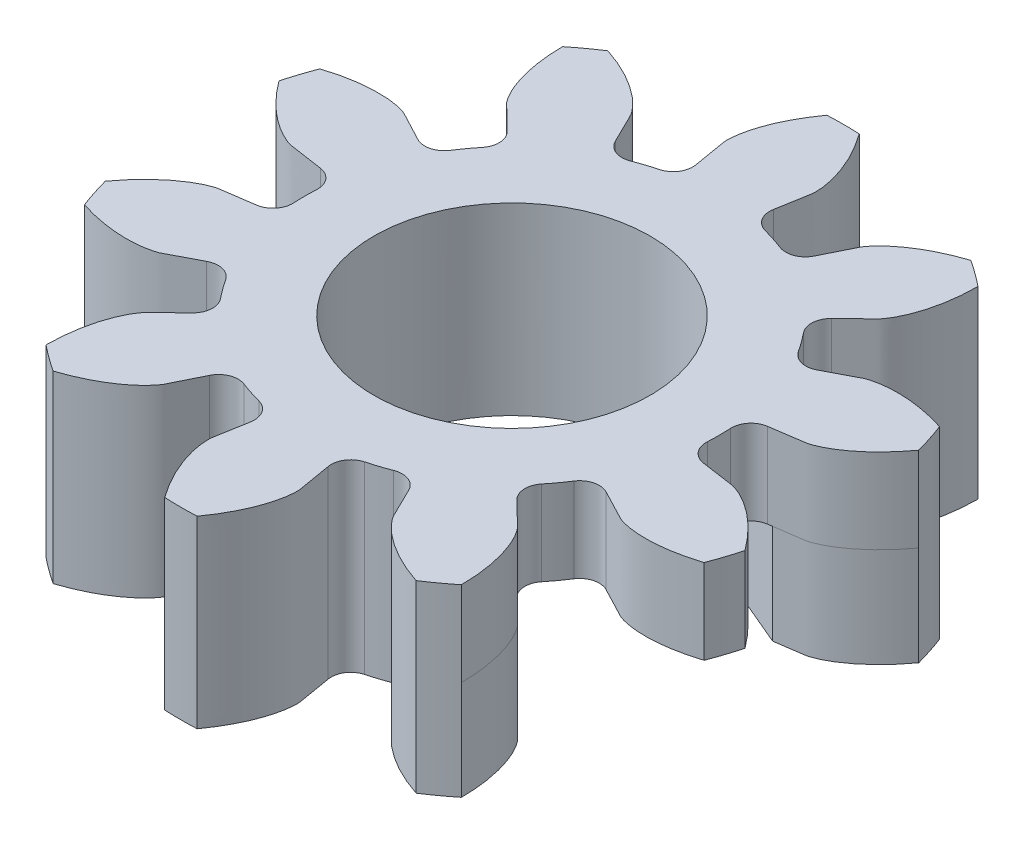
SolidWorks part; units mm, degrees
ref_plane "前视基准面" through (0, 0, 0) normal (0, 0, 1) x (1, 0, 0)
ref_plane "上视基准面" through (0, 0, 0) normal (0, 1, 0) x (1, 0, 0)
ref_plane "右视基准面" through (0, 0, 0) normal (1, 0, 0) x (0, 0, -1)
ref_plane "基准面1" through (0, -5, 0) normal (0, -1, 0) x (1, 0, 0)
sketch "草图1" plane through (0, -5, 0) normal (0, -1, 0) x (1, 0, 0)
  line L0 (6.1909, -0.8847) -> (3.0118, -2.2341)
  line L1 (1.1234, 3.5778) -> (4.4885, 4.3547)
  arc A0 (5.6398, 7.0137) -> (8.6853, -2.3592) centre (0, 0) ccw
  arc A1 (3.0118, -2.2341) -> (1.1234, 3.5778) centre (0, 0) ccw
  spline S0 degree 3 poles (6.1909, -0.8847) (6.5939, -0.9417) (6.9799, -0.9969) (7.0084, -1.0053) (7.0566, -1.0179) (7.1132, -1.0368) (7.1879, -1.0654) (7.2763, -1.1046) (7.3786, -1.1562) (7.4935, -1.2216) (7.6198, -1.3021) (7.7564, -1.399) (7.9018, -1.5135) (8.0545, -1.6467) (8.2131, -1.7996) (8.3759, -1.9733) (8.5348, -2.1595) (8.6367, -2.2945) (8.6853, -2.3592) knots 0.057559 0.057559 0.057559 0.057559 0.176646 0.200647 0.231632 0.268294 0.309864 0.355822 0.405784 0.459451 0.516584 0.576985 0.640485 0.70694 0.776225 0.848227 0.922848 0.990951 0.990951 0.990951 0.990951
  spline S1 degree 3 poles (4.4885, 4.3547) (4.7811, 4.6376) (5.0609, 4.9092) (5.079, 4.9328) (5.1106, 4.9713) (5.1453, 5.0198) (5.1889, 5.0868) (5.2373, 5.1705) (5.2898, 5.2724) (5.3443, 5.3928) (5.3992, 5.5322) (5.4528, 5.6909) (5.5031, 5.869) (5.5483, 6.0665) (5.5868, 6.2834) (5.6164, 6.5196) (5.6355, 6.7637) (5.6386, 6.9328) (5.6398, 7.0137) knots 0.057559 0.057559 0.057559 0.057559 0.176646 0.200647 0.231632 0.268294 0.309864 0.355822 0.405784 0.459451 0.516584 0.576985 0.640485 0.70694 0.776225 0.848227 0.922848 0.990951 0.990951 0.990951 0.990951
extrude "凸台-拉伸1" add sketch "草图1" against normal blind 2.7
sketch "草图2" plane through (0, -2.3, 0) normal (0, 1, 0) x (-1, 0, 0)
  arc A0 (-5.6398, 7.0137) -> (-8.6853, -2.3592) centre (0, 0) cw
  arc A1 (-5.5682, -0.797) -> (-5.5682, 0.797) centre (0, 0) cw
  arc A2 (-8.6853, 2.3592) -> (-8.4133, 3.1964) centre (0, 0) cw
  arc A3 (-4.9733, 2.6281) -> (-4.0363, 3.9178) centre (0, 0) cw
  spline S0 degree 3 poles (-5.5682, -0.797) (-6.2247, -0.8893) (-6.9705, -0.9942) (-7.0084, -1.0053) (-7.0566, -1.0179) (-7.1132, -1.0368) (-7.1879, -1.0654) (-7.2763, -1.1046) (-7.3786, -1.1562) (-7.4935, -1.2216) (-7.6198, -1.3021) (-7.7564, -1.399) (-7.9018, -1.5135) (-8.0545, -1.6467) (-8.2131, -1.7996) (-8.3759, -1.9733) (-8.5348, -2.1595) (-8.6367, -2.2945) (-8.6853, -2.3592) knots 0 0 0 0 0.176646 0.200647 0.231632 0.268294 0.309864 0.355822 0.405784 0.459451 0.516584 0.576985 0.640485 0.70694 0.776225 0.848227 0.922848 0.990951 0.990951 0.990951 0.990951
  spline S1 degree 3 poles (-5.5682, 0.797) (-6.2247, 0.8893) (-6.9705, 0.9942) (-7.0084, 1.0053) (-7.0566, 1.0179) (-7.1132, 1.0368) (-7.1879, 1.0654) (-7.2763, 1.1046) (-7.3786, 1.1562) (-7.4935, 1.2216) (-7.6198, 1.3021) (-7.7564, 1.399) (-7.9018, 1.5135) (-8.0545, 1.6467) (-8.2131, 1.7996) (-8.3759, 1.9733) (-8.5348, 2.1595) (-8.6367, 2.2945) (-8.6853, 2.3592) knots 0 0 0 0 0.176646 0.200647 0.231632 0.268294 0.309864 0.355822 0.405784 0.459451 0.516584 0.576985 0.640485 0.70694 0.776225 0.848227 0.922848 0.990951 0.990951 0.990951 0.990951
  spline S2 degree 3 poles (-4.9733, 2.6281) (-5.5587, 2.9393) (-6.2236, 3.2928) (-6.2608, 3.3061) (-6.3072, 3.3243) (-6.3641, 3.3422) (-6.4413, 3.363) (-6.5359, 3.3832) (-6.649, 3.4016) (-6.7804, 3.4163) (-6.9299, 3.4254) (-7.0973, 3.4273) (-7.2823, 3.4201) (-7.4841, 3.4021) (-7.7023, 3.3717) (-7.9361, 3.3268) (-8.1741, 3.2696) (-8.336, 3.2203) (-8.4133, 3.1964) knots 0 0 0 0 0.176646 0.200647 0.231632 0.268294 0.309864 0.355822 0.405784 0.459451 0.516584 0.576985 0.640485 0.70694 0.776225 0.848227 0.922848 0.990951 0.990951 0.990951 0.990951
  spline S3 degree 3 poles (-4.0363, 3.9178) (-4.5132, 4.3783) (-5.0549, 4.9014) (-5.079, 4.9328) (-5.1106, 4.9713) (-5.1453, 5.0198) (-5.1889, 5.0868) (-5.2373, 5.1705) (-5.2898, 5.2724) (-5.3443, 5.3928) (-5.3992, 5.5322) (-5.4528, 5.6909) (-5.5031, 5.869) (-5.5483, 6.0665) (-5.5868, 6.2834) (-5.6164, 6.5196) (-5.6355, 6.7637) (-5.6386, 6.9328) (-5.6398, 7.0137) knots 0 0 0 0 0.176646 0.200647 0.231632 0.268294 0.309864 0.355822 0.405784 0.459451 0.516584 0.576985 0.640485 0.70694 0.776225 0.848227 0.922848 0.990951 0.990951 0.990951 0.990951
extrude "凸台-拉伸2" add sketch "草图2" along normal blind 2.3
sketch "草图3" plane through (0, 0, 0) normal (0, 1, 0) x (-1, 0, 0)
  arc A0 (-2.4787, 5.0494) -> (-0.9626, 5.542) centre (0, 0) cw
  arc A1 (-0.4401, 8.9892) -> (-4.9277, 7.5311) centre (0, 0) ccw
  spline S0 degree 3 poles (-2.4787, 5.0494) (-2.7694, 5.6453) (-3.0995, 6.3221) (-3.1219, 6.3547) (-3.1487, 6.3967) (-3.1842, 6.4446) (-3.2344, 6.5068) (-3.2991, 6.5788) (-3.3798, 6.6602) (-3.4774, 6.7492) (-3.593, 6.8445) (-3.7274, 6.9445) (-3.8812, 7.0473) (-4.0551, 7.1514) (-4.2495, 7.2551) (-4.465, 7.3561) (-4.6912, 7.4498) (-4.8511, 7.505) (-4.9277, 7.5311) knots 0 0 0 0 0.176646 0.200647 0.231632 0.268294 0.309864 0.355822 0.405784 0.459451 0.516584 0.576985 0.640485 0.70694 0.776225 0.848227 0.922848 0.990951 0.990951 0.990951 0.990951
  spline S1 degree 3 poles (-0.9626, 5.542) (-1.0777, 6.1949) (-1.2085, 6.9365) (-1.2096, 6.9761) (-1.2125, 7.0258) (-1.212, 7.0854) (-1.2079, 7.1653) (-1.1979, 7.2615) (-1.1805, 7.3748) (-1.1538, 7.5042) (-1.1163, 7.6493) (-1.0664, 7.8091) (-1.0024, 7.9827) (-0.9229, 8.1692) (-0.8265, 8.3672) (-0.7116, 8.5757) (-0.5836, 8.7844) (-0.4867, 8.9231) (-0.4401, 8.9892) knots 0 0 0 0 0.176646 0.200647 0.231632 0.268294 0.309864 0.355822 0.405784 0.459451 0.516584 0.576985 0.640485 0.70694 0.776225 0.848227 0.922848 0.990951 0.990951 0.990951 0.990951
extrude "切除-拉伸1" cut sketch "草图3" against normal through all
sketch "草图4" plane through (0, 0, 0) normal (0, 1, 0) x (-1, 0, 0)
  arc A0 (0.9626, 5.542) -> (2.4787, 5.0494) centre (0, 0) cw
  arc A1 (4.9277, 7.5311) -> (0.4401, 8.9892) centre (0, 0) ccw
  spline S0 degree 3 poles (0.9626, 5.542) (1.0777, 6.1949) (1.2085, 6.9365) (1.2096, 6.9761) (1.2125, 7.0258) (1.212, 7.0854) (1.2079, 7.1653) (1.1979, 7.2615) (1.1805, 7.3748) (1.1538, 7.5042) (1.1163, 7.6493) (1.0664, 7.8091) (1.0024, 7.9827) (0.9229, 8.1692) (0.8265, 8.3672) (0.7116, 8.5757) (0.5836, 8.7844) (0.4867, 8.9231) (0.4401, 8.9892) knots 0 0 0 0 0.176646 0.200647 0.231632 0.268294 0.309864 0.355822 0.405784 0.459451 0.516584 0.576985 0.640485 0.70694 0.776225 0.848227 0.922848 0.990951 0.990951 0.990951 0.990951
  spline S1 degree 3 poles (2.4787, 5.0494) (2.7694, 5.6453) (3.0995, 6.3221) (3.1219, 6.3547) (3.1487, 6.3967) (3.1842, 6.4446) (3.2344, 6.5068) (3.2991, 6.5788) (3.3798, 6.6602) (3.4774, 6.7492) (3.593, 6.8445) (3.7274, 6.9445) (3.8812, 7.0473) (4.0551, 7.1514) (4.2495, 7.2551) (4.465, 7.3561) (4.6912, 7.4498) (4.8511, 7.505) (4.9277, 7.5311) knots 0 0 0 0 0.176646 0.200647 0.231632 0.268294 0.309864 0.355822 0.405784 0.459451 0.516584 0.576985 0.640485 0.70694 0.776225 0.848227 0.922848 0.990951 0.990951 0.990951 0.990951
extrude "切除-拉伸2" cut sketch "草图4" against normal through all
sketch "草图5" plane through (0, 0, 0) normal (0, 1, 0) x (-1, 0, 0)
  arc A0 (4.0363, 3.9178) -> (4.9733, 2.6281) centre (0, 0) cw
  arc A1 (8.4133, 3.1964) -> (5.6398, 7.0137) centre (0, 0) ccw
  spline S0 degree 3 poles (4.0363, 3.9178) (4.5132, 4.3783) (5.0549, 4.9014) (5.079, 4.9328) (5.1106, 4.9713) (5.1453, 5.0198) (5.1889, 5.0868) (5.2373, 5.1705) (5.2898, 5.2724) (5.3443, 5.3928) (5.3992, 5.5322) (5.4528, 5.6909) (5.5031, 5.869) (5.5483, 6.0665) (5.5868, 6.2834) (5.6164, 6.5196) (5.6355, 6.7637) (5.6386, 6.9328) (5.6398, 7.0137) knots 0 0 0 0 0.176646 0.200647 0.231632 0.268294 0.309864 0.355822 0.405784 0.459451 0.516584 0.576985 0.640485 0.70694 0.776225 0.848227 0.922848 0.990951 0.990951 0.990951 0.990951
  spline S1 degree 3 poles (4.9733, 2.6281) (5.5587, 2.9393) (6.2236, 3.2928) (6.2608, 3.3061) (6.3072, 3.3243) (6.3641, 3.3422) (6.4413, 3.363) (6.5359, 3.3832) (6.649, 3.4016) (6.7804, 3.4163) (6.9299, 3.4254) (7.0973, 3.4273) (7.2823, 3.4201) (7.4841, 3.4021) (7.7023, 3.3717) (7.9361, 3.3268) (8.1741, 3.2696) (8.336, 3.2203) (8.4133, 3.1964) knots 0 0 0 0 0.176646 0.200647 0.231632 0.268294 0.309864 0.355822 0.405784 0.459451 0.516584 0.576985 0.640485 0.70694 0.776225 0.848227 0.922848 0.990951 0.990951 0.990951 0.990951
extrude "切除-拉伸3" cut sketch "草图5" against normal through all
sketch "草图6" plane through (0, 0, 0) normal (0, 1, 0) x (-1, 0, 0)
  arc A0 (5.5682, 0.797) -> (5.5682, -0.797) centre (0, 0) cw
  arc A1 (8.6853, -2.3592) -> (8.6853, 2.3592) centre (0, 0) ccw
  spline S0 degree 3 poles (5.5682, 0.797) (6.2247, 0.8893) (6.9705, 0.9942) (7.0084, 1.0053) (7.0566, 1.0179) (7.1132, 1.0368) (7.1879, 1.0654) (7.2763, 1.1046) (7.3786, 1.1562) (7.4935, 1.2216) (7.6198, 1.3021) (7.7564, 1.399) (7.9018, 1.5135) (8.0545, 1.6467) (8.2131, 1.7996) (8.3759, 1.9733) (8.5348, 2.1595) (8.6367, 2.2945) (8.6853, 2.3592) knots 0 0 0 0 0.176646 0.200647 0.231632 0.268294 0.309864 0.355822 0.405784 0.459451 0.516584 0.576985 0.640485 0.70694 0.776225 0.848227 0.922848 0.990951 0.990951 0.990951 0.990951
  spline S1 degree 3 poles (5.5682, -0.797) (6.2247, -0.8893) (6.9705, -0.9942) (7.0084, -1.0053) (7.0566, -1.0179) (7.1132, -1.0368) (7.1879, -1.0654) (7.2763, -1.1046) (7.3786, -1.1562) (7.4935, -1.2216) (7.6198, -1.3021) (7.7564, -1.399) (7.9018, -1.5135) (8.0545, -1.6467) (8.2131, -1.7996) (8.3759, -1.9733) (8.5348, -2.1595) (8.6367, -2.2945) (8.6853, -2.3592) knots 0 0 0 0 0.176646 0.200647 0.231632 0.268294 0.309864 0.355822 0.405784 0.459451 0.516584 0.576985 0.640485 0.70694 0.776225 0.848227 0.922848 0.990951 0.990951 0.990951 0.990951
extrude "切除-拉伸4" cut sketch "草图6" against normal through all
sketch "草图7" plane through (0, 0, 0) normal (0, 1, 0) x (-1, 0, 0)
  arc A0 (4.9733, -2.6281) -> (4.0363, -3.9178) centre (0, 0) cw
  arc A1 (5.6398, -7.0137) -> (8.4133, -3.1964) centre (0, 0) ccw
  spline S0 degree 3 poles (4.9733, -2.6281) (5.5587, -2.9393) (6.2236, -3.2928) (6.2608, -3.3061) (6.3072, -3.3243) (6.3641, -3.3422) (6.4413, -3.363) (6.5359, -3.3832) (6.649, -3.4016) (6.7804, -3.4163) (6.9299, -3.4254) (7.0973, -3.4273) (7.2823, -3.4201) (7.4841, -3.4021) (7.7023, -3.3717) (7.9361, -3.3268) (8.1741, -3.2696) (8.336, -3.2203) (8.4133, -3.1964) knots 0 0 0 0 0.176646 0.200647 0.231632 0.268294 0.309864 0.355822 0.405784 0.459451 0.516584 0.576985 0.640485 0.70694 0.776225 0.848227 0.922848 0.990951 0.990951 0.990951 0.990951
  spline S1 degree 3 poles (4.0363, -3.9178) (4.5132, -4.3783) (5.0549, -4.9014) (5.079, -4.9328) (5.1106, -4.9713) (5.1453, -5.0198) (5.1889, -5.0868) (5.2373, -5.1705) (5.2898, -5.2724) (5.3443, -5.3928) (5.3992, -5.5322) (5.4528, -5.6909) (5.5031, -5.869) (5.5483, -6.0665) (5.5868, -6.2834) (5.6164, -6.5196) (5.6355, -6.7637) (5.6386, -6.9328) (5.6398, -7.0137) knots 0 0 0 0 0.176646 0.200647 0.231632 0.268294 0.309864 0.355822 0.405784 0.459451 0.516584 0.576985 0.640485 0.70694 0.776225 0.848227 0.922848 0.990951 0.990951 0.990951 0.990951
extrude "切除-拉伸5" cut sketch "草图7" against normal through all
sketch "草图8" plane through (0, 0, 0) normal (0, 1, 0) x (-1, 0, 0)
  arc A0 (2.4787, -5.0494) -> (0.9626, -5.542) centre (0, 0) cw
  arc A1 (0.4401, -8.9892) -> (4.9277, -7.5311) centre (0, 0) ccw
  spline S0 degree 3 poles (2.4787, -5.0494) (2.7694, -5.6453) (3.0995, -6.3221) (3.1219, -6.3547) (3.1487, -6.3967) (3.1842, -6.4446) (3.2344, -6.5068) (3.2991, -6.5788) (3.3798, -6.6602) (3.4774, -6.7492) (3.593, -6.8445) (3.7274, -6.9445) (3.8812, -7.0473) (4.0551, -7.1514) (4.2495, -7.2551) (4.465, -7.3561) (4.6912, -7.4498) (4.8511, -7.505) (4.9277, -7.5311) knots 0 0 0 0 0.176646 0.200647 0.231632 0.268294 0.309864 0.355822 0.405784 0.459451 0.516584 0.576985 0.640485 0.70694 0.776225 0.848227 0.922848 0.990951 0.990951 0.990951 0.990951
  spline S1 degree 3 poles (0.9626, -5.542) (1.0777, -6.1949) (1.2085, -6.9365) (1.2096, -6.9761) (1.2125, -7.0258) (1.212, -7.0854) (1.2079, -7.1653) (1.1979, -7.2615) (1.1805, -7.3748) (1.1538, -7.5042) (1.1163, -7.6493) (1.0664, -7.8091) (1.0024, -7.9827) (0.9229, -8.1692) (0.8265, -8.3672) (0.7116, -8.5757) (0.5836, -8.7844) (0.4867, -8.9231) (0.4401, -8.9892) knots 0 0 0 0 0.176646 0.200647 0.231632 0.268294 0.309864 0.355822 0.405784 0.459451 0.516584 0.576985 0.640485 0.70694 0.776225 0.848227 0.922848 0.990951 0.990951 0.990951 0.990951
extrude "切除-拉伸6" cut sketch "草图8" against normal through all
sketch "草图9" plane through (0, 0, 0) normal (0, 1, 0) x (-1, 0, 0)
  arc A0 (-0.9626, -5.542) -> (-2.4787, -5.0494) centre (0, 0) cw
  arc A1 (-4.9277, -7.5311) -> (-0.4401, -8.9892) centre (0, 0) ccw
  spline S0 degree 3 poles (-0.9626, -5.542) (-1.0777, -6.1949) (-1.2085, -6.9365) (-1.2096, -6.9761) (-1.2125, -7.0258) (-1.212, -7.0854) (-1.2079, -7.1653) (-1.1979, -7.2615) (-1.1805, -7.3748) (-1.1538, -7.5042) (-1.1163, -7.6493) (-1.0664, -7.8091) (-1.0024, -7.9827) (-0.9229, -8.1692) (-0.8265, -8.3672) (-0.7116, -8.5757) (-0.5836, -8.7844) (-0.4867, -8.9231) (-0.4401, -8.9892) knots 0 0 0 0 0.176646 0.200647 0.231632 0.268294 0.309864 0.355822 0.405784 0.459451 0.516584 0.576985 0.640485 0.70694 0.776225 0.848227 0.922848 0.990951 0.990951 0.990951 0.990951
  spline S1 degree 3 poles (-2.4787, -5.0494) (-2.7694, -5.6453) (-3.0995, -6.3221) (-3.1219, -6.3547) (-3.1487, -6.3967) (-3.1842, -6.4446) (-3.2344, -6.5068) (-3.2991, -6.5788) (-3.3798, -6.6602) (-3.4774, -6.7492) (-3.593, -6.8445) (-3.7274, -6.9445) (-3.8812, -7.0473) (-4.0551, -7.1514) (-4.2495, -7.2551) (-4.465, -7.3561) (-4.6912, -7.4498) (-4.8511, -7.505) (-4.9277, -7.5311) knots 0 0 0 0 0.176646 0.200647 0.231632 0.268294 0.309864 0.355822 0.405784 0.459451 0.516584 0.576985 0.640485 0.70694 0.776225 0.848227 0.922848 0.990951 0.990951 0.990951 0.990951
extrude "切除-拉伸7" cut sketch "草图9" against normal through all
sketch "草图10" plane through (0, 0, 0) normal (0, 1, 0) x (-1, 0, 0)
  arc A0 (-4.0363, -3.9178) -> (-4.9733, -2.6281) centre (0, 0) cw
  arc A1 (-8.4133, -3.1964) -> (-5.6398, -7.0137) centre (0, 0) ccw
  spline S0 degree 3 poles (-4.0363, -3.9178) (-4.5132, -4.3783) (-5.0549, -4.9014) (-5.079, -4.9328) (-5.1106, -4.9713) (-5.1453, -5.0198) (-5.1889, -5.0868) (-5.2373, -5.1705) (-5.2898, -5.2724) (-5.3443, -5.3928) (-5.3992, -5.5322) (-5.4528, -5.6909) (-5.5031, -5.869) (-5.5483, -6.0665) (-5.5868, -6.2834) (-5.6164, -6.5196) (-5.6355, -6.7637) (-5.6386, -6.9328) (-5.6398, -7.0137) knots 0 0 0 0 0.176646 0.200647 0.231632 0.268294 0.309864 0.355822 0.405784 0.459451 0.516584 0.576985 0.640485 0.70694 0.776225 0.848227 0.922848 0.990951 0.990951 0.990951 0.990951
  spline S1 degree 3 poles (-4.9733, -2.6281) (-5.5587, -2.9393) (-6.2236, -3.2928) (-6.2608, -3.3061) (-6.3072, -3.3243) (-6.3641, -3.3422) (-6.4413, -3.363) (-6.5359, -3.3832) (-6.649, -3.4016) (-6.7804, -3.4163) (-6.9299, -3.4254) (-7.0973, -3.4273) (-7.2823, -3.4201) (-7.4841, -3.4021) (-7.7023, -3.3717) (-7.9361, -3.3268) (-8.1741, -3.2696) (-8.336, -3.2203) (-8.4133, -3.1964) knots 0 0 0 0 0.176646 0.200647 0.231632 0.268294 0.309864 0.355822 0.405784 0.459451 0.516584 0.576985 0.640485 0.70694 0.776225 0.848227 0.922848 0.990951 0.990951 0.990951 0.990951
extrude "切除-拉伸8" cut sketch "草图10" against normal through all
sketch "草图11" plane through (0, 0, 0) normal (0, 0, 1) x (1, 0, 0)
  line L0 (3.75, 0) -> (0, 0)
  line L1 (0, 0) -> (0, -5)
  line L2 (0, -5) -> (3.75, -5)
  line L3 (3.75, -5) -> (3.75, 0)
  line L4 (0, 0) -> (0, -5) construction
revolve "切除-旋转1" cut sketch "草图11" angle 360 about L4
fillet "圆角1" radius 0.5314 20 edges at (-0.9626, -2.5, -5.542) (-5.5682, -2.5, -0.797) (4.9733, -2.5, -2.6281) (5.5682, -1.15, 0.797) (-4.0363, -2.5, -3.9178) (4.9733, -1.15, 2.6281) (2.4787, -2.5, -5.0494) (4.0363, -1.15, 3.9178) (-5.5682, -2.5, 0.797) (2.4787, -2.5, 5.0494) (-4.9733, -2.5, -2.6281) (0.9626, -2.5, 5.542) (-2.4787, -2.5, -5.0494) (-0.9626, -2.5, 5.542) (0.9626, -2.5, -5.542) (-2.4787, -2.5, 5.0494) (4.0363, -2.5, -3.9178) (-4.0363, -2.5, 3.9178) (5.5682, -1.15, -0.797) (-4.9733, -2.5, 2.6281)
